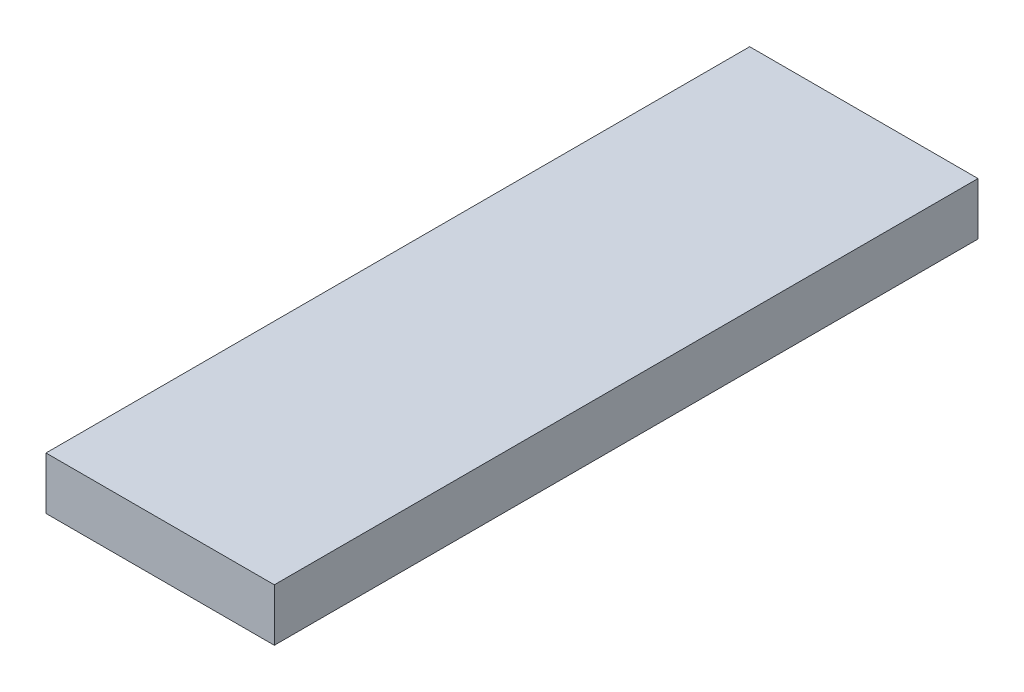
SolidWorks part; units mm, degrees
material "A-Glass Fiber"
ref_plane "Front Plane" through (0, 0, 0) normal (0, 0, 1) x (1, 0, 0)
ref_plane "Top Plane" through (0, 0, 0) normal (0, 1, 0) x (1, 0, 0)
ref_plane "Right Plane" through (0, 0, 0) normal (1, 0, 0) x (0, 0, -1)
sketch "Sketch1" plane through (0, 0, 0) normal (0, 1, 0) x (1, 0, 0)
  line L1 (-193.675, 596.9) -> (193.675, 596.9)
  line L2 (-193.675, 596.9) -> (-193.675, -596.9)
  line L3 (-193.675, -596.9) -> (193.675, -596.9)
  line L4 (193.675, 596.9) -> (193.675, -596.9)
  line L5 (-193.675, 596.9) -> (193.675, -596.9) construction
  line L6 (-193.675, -596.9) -> (193.675, 596.9) construction
  point P0 (0, 0)
  dimension "D1" = 387.35
  dimension "D2" = 1193.8
extrude "Boss-Extrude1" add sketch "Sketch1" along normal blind 88.9
